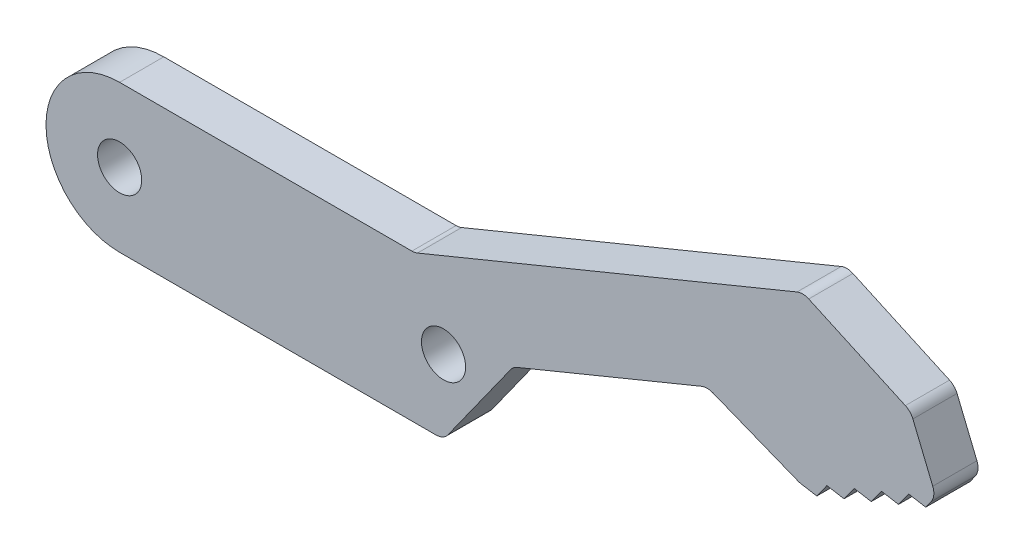
SolidWorks part; units mm, degrees
ref_plane "Front Plane" through (0, 0, 0) normal (0, 0, 1) x (1, 0, 0)
ref_plane "Top Plane" through (0, 0, 0) normal (0, 1, 0) x (1, 0, 0)
ref_plane "Right Plane" through (0, 0, 0) normal (1, 0, 0) x (0, 0, -1)
sketch "Sketch1" plane through (0, 0, 0) normal (0, 0, 1) x (1, 0, 0)
  line L0 (0, 0) -> (22, 0) construction
  line L1 (0, 5) -> (22, 5)
  line L2 (0, -5) -> (22, -5)
  line L3 (20.05, 5) -> (23.9914, -4.5863) construction
  line L4 (20.05, 5) -> (51.4959, 17.929) construction
  line L5 (23.9914, -4.5863) -> (55.4373, 8.3426) construction
  line L6 (51.4959, 17.929) -> (55.4373, 8.3426) construction
  line L7 (20.05, 5) -> (46.409, 15.8375)
  line L8 (46.409, 15.8375) -> (53.7261, 12.5046)
  line L9 (53.7261, 12.5046) -> (55.4373, 8.3426)
  line L10 (55.4373, 8.3426) -> (46.1885, 4.54) construction
  line L11 (46.1885, 4.54) -> (39.9002, 7.0361)
  line L12 (39.9002, 7.0361) -> (26.7299, 1.6211)
  line L13 (46.1885, 4.54) -> (47.351, 4.3422)
  line L14 (47.351, 4.3422) -> (48.0382, 5.3005)
  line L15 (47.351, 4.3422) -> (54.7501, 7.3843) construction
  line L16 (48.0382, 5.3005) -> (49.2008, 5.1027)
  line L17 (49.2008, 5.1027) -> (49.888, 6.0611)
  line L18 (49.888, 6.0611) -> (51.0505, 5.8633)
  line L19 (51.0505, 5.8633) -> (51.7378, 6.8216)
  line L20 (51.7378, 6.8216) -> (52.9003, 6.6238)
  line L21 (52.9003, 6.6238) -> (53.5875, 7.5821)
  line L22 (53.5875, 7.5821) -> (54.7501, 7.3843)
  line L23 (54.7501, 7.3843) -> (55.4373, 8.3426)
  line L24 (26.7299, 1.6211) -> (22, -5)
  arc A0 (0, 5) -> (0, -5) centre (0, 0) ccw
  arc A1 (22, -5) -> (22, 5) centre (22, 0) ccw
  circle A2 centre (0, 0) radius 1.5
  circle A3 centre (22, 0) radius 1.5
  point P3 (11, 0)
  dimension "D11" = 3
  dimension "D1" = 10
  dimension "D2" = 22
  dimension "D3" = 157.65
  dimension "D4" = 1.95
  dimension "D5" = 34
  dimension "D6" = 14.24
  dimension "D7" = 10
  dimension "D8" = 4.5
  dimension "D9" = 136
  dimension "D10" = 5.5
  dimension "D12" = 2
  dimension "D13" = 0.625
  dimension "D14" = 8
extrude "Boss-Extrude1" add sketch "Sketch1" along normal blind 3 contours A1 L1 A0 L2 A3 A2 | A1 L12 L11 L13 L14 L16 L17 L18 L19 L20 L21 L22 L23 L9 L8 L7 L1
fillet "Fillet1" radius 1 8 edges at (46.1885, 4.54, 1.5) (55.4373, 8.3426, 1.5) (53.7261, 12.5046, 1.5) (46.409, 15.8375, 1.5) (20.05, 5, 1.5) (39.9002, 7.0361, 1.5) (26.7299, 1.6211, 1.5) (22, -5, 1.5)
